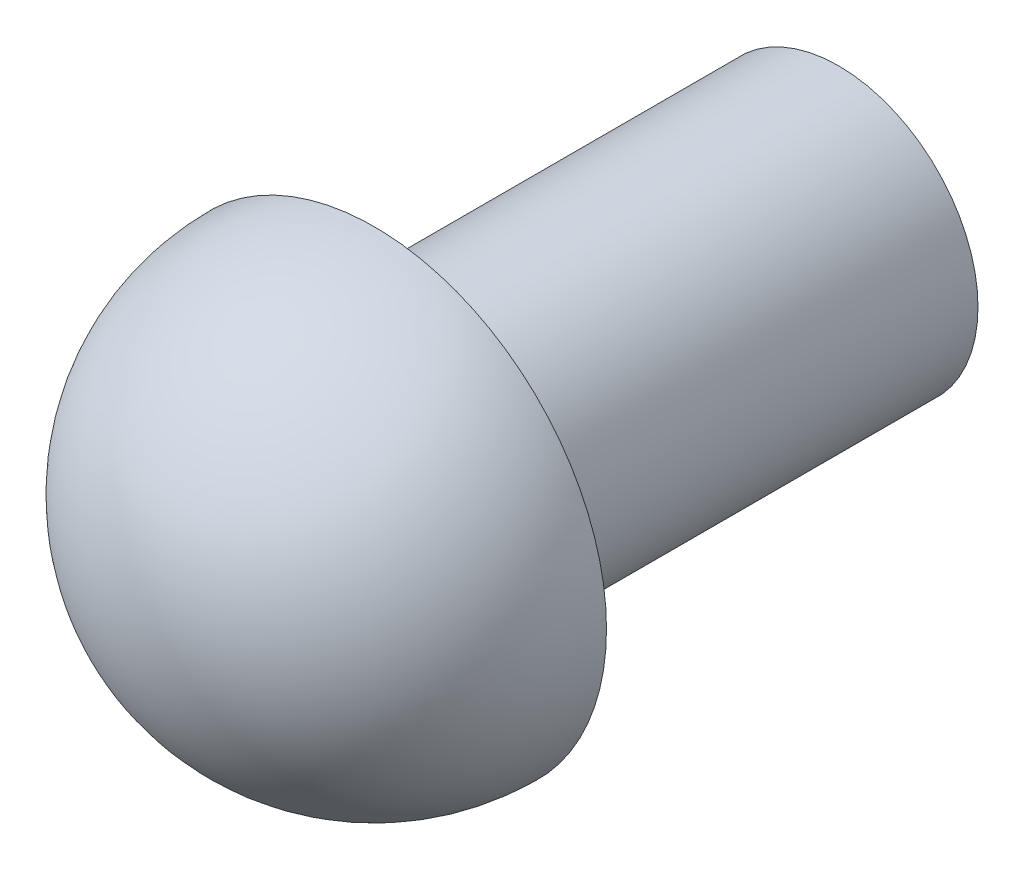
SolidWorks part; units mm, degrees
ref_plane "Front Plane" through (0, 0, 0) normal (0, 0, 1) x (1, 0, 0)
ref_plane "Top Plane" through (0, 0, 0) normal (0, 1, 0) x (1, 0, 0)
ref_plane "Right Plane" through (0, 0, 0) normal (1, 0, 0) x (0, 0, -1)
sketch "Sketch2" plane through (0, 0, 0) normal (0, 0, 1) x (1, 0, 0)
  line L0 (0, 0) -> (0, 10)
  line L1 (0, 0) -> (0, 27.3788) construction
  arc A0 (0, 10) -> (0, 0) centre (0, 5) ccw
  dimension "D1" = 10
revolve "Revolve1" add sketch "Sketch2" angle 180 about L1
sketch "Sketch5" plane through (0, 0, 0) normal (0, 0, -1) x (-1, 0, 0)
  line L0 (-5, 5) -> (0, 5)
  circle A0 centre (0, 5) radius 5 construction
  circle A1 centre (0, 5) radius 3
extrude "Boss-Extrude1" add sketch "Sketch5" along normal blind 10
